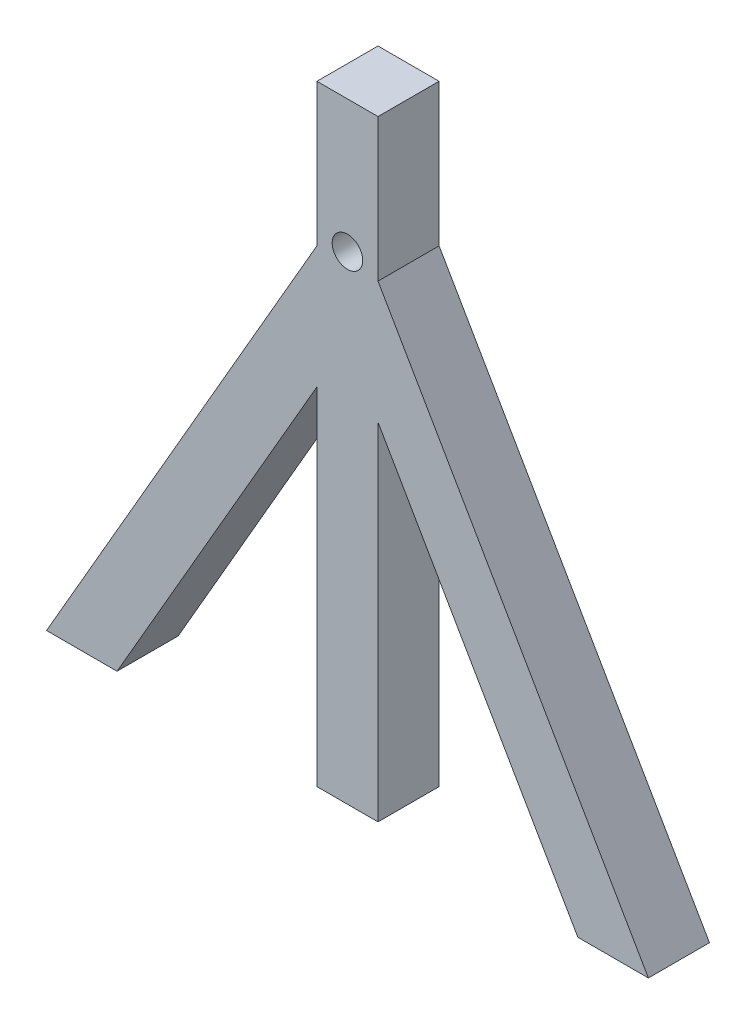
SolidWorks part; units mm, degrees
material "Mahogany"
ref_plane "Front Plane" through (0, 0, 0) normal (0, 0, 1) x (1, 0, 0)
ref_plane "Top Plane" through (0, 0, 0) normal (0, 1, 0) x (1, 0, 0)
ref_plane "Right Plane" through (0, 0, 0) normal (1, 0, 0) x (0, 0, -1)
sketch "Sketch1" plane through (0, 0, 0) normal (0, 0, 1) x (1, 0, 0)
  line L0 (-15, 20) -> (-113.1495, -150)
  line L1 (-15, -150) -> (15, -150)
  line L2 (-15, -150) -> (-15, 20)
  line L3 (-15, 150) -> (15, 150)
  line L4 (15, -150) -> (15, 20)
  line L5 (-15, -150) -> (15, 150) construction
  line L6 (-15, 150) -> (15, -150) construction
  line L7 (-113.1495, -150) -> (-147.7906, -150)
  line L8 (-147.7906, -150) -> (-15, 80)
  line L9 (-15, 80) -> (-15, 150)
  line L10 (0, -150) -> (0, -272.9743) construction
  line L11 (15, 20) -> (113.1495, -150)
  line L12 (113.1495, -150) -> (147.7906, -150)
  line L13 (147.7906, -150) -> (15, 80)
  line L14 (15, 80) -> (15, 150)
  point P0 (0, 0)
  dimension "D1" = 300
  dimension "D2" = 30
  dimension "D3" = 30
  dimension "D4" = 170
  dimension "D5" = 30
extrude "Boss-Extrude1" add sketch "Sketch1" along normal blind 30
sketch "Sketch2" plane through (0, 0, 30) normal (0, 0, 1) x (1, 0, 0)
  line L0 (15, 150) -> (-15, 150) construction
  circle A0 centre (0, 85) radius 7.5
  dimension "D2" = 15
  dimension "D1" = 65
extrude "Cut-Extrude1" cut sketch "Sketch2" against normal through all
